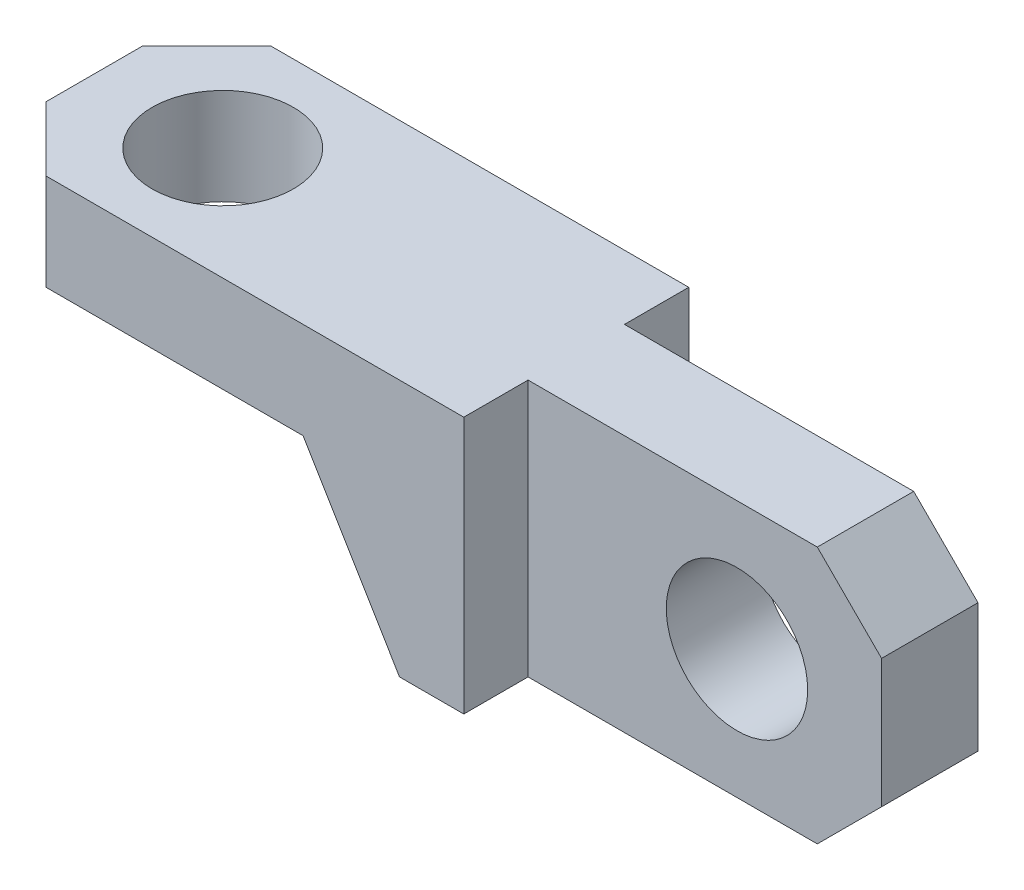
SolidWorks part; units mm, degrees
ref_plane "Front Plane" through (0, 0, 0) normal (0, 0, 1) x (1, 0, 0)
ref_plane "Top Plane" through (0, 0, 0) normal (0, 1, 0) x (1, 0, 0)
ref_plane "Right Plane" through (0, 0, 0) normal (1, 0, 0) x (0, 0, -1)
sketch "Sketch1" plane through (0, 0, 0) normal (0, 1, 0) x (1, 0, 0)
  line L0 (5.08, 0) -> (5.08, 8.89) construction
  line L1 (0, 0) -> (19.05, 0)
  line L2 (0, 0) -> (0, 8.89)
  line L3 (0, 8.89) -> (19.05, 8.89)
  line L4 (19.05, 0) -> (19.05, 8.89) construction
  line L5 (19.05, 6.35) -> (33.02, 6.35)
  line L6 (19.05, 8.89) -> (19.05, 6.35)
  line L7 (19.05, 0) -> (19.05, 2.54)
  line L8 (19.05, 2.54) -> (33.02, 2.54)
  line L9 (33.02, 2.54) -> (33.02, 6.35)
  circle A0 centre (5.08, 4.445) radius 2.794
  dimension "D3" = 5.588
  dimension "D1" = 19.05
  dimension "D2" = 8.89
  dimension "D4" = 5.08
  dimension "D5" = 3.81
  dimension "D6" = 13.97
extrude "base" add sketch "Sketch1" along normal blind 10.16
sketch "Sketch2" plane through (0, 0, -2.54) normal (0, 0, 1) x (1, 0, 0)
  line L0 (27.305, 10.16) -> (27.305, 0) construction
  line L1 (19.05, 10.16) -> (33.02, 10.16) construction
  line L2 (19.05, 0) -> (33.02, 0) construction
  line L3 (33.02, 10.16) -> (33.02, 0) construction
  circle A0 centre (27.305, 5.08) radius 2.794
  point P6 (23.992, 5.08)
  dimension "D1" = 5.588
  dimension "D2" = 5.715
extrude "latch_hole" cut sketch "Sketch2" against normal up to next
sketch "Sketch4" plane through (0, 0, 0) normal (0, 0, 1) x (1, 0, 0)
  line L0 (0, 6.35) -> (12.7, 6.35)
  line L1 (0, 10.16) -> (0, 0) construction
  line L2 (12.7, 6.35) -> (16.51, 0)
  line L3 (0, 0) -> (19.05, 0) construction
  line L4 (0, 6.35) -> (0, 0)
  line L5 (0, 0) -> (16.51, 0)
  dimension "D1" = 3.81
  dimension "D2" = 12.7
  dimension "D3" = 16.51
extrude "servo_arm_hole" cut sketch "Sketch4" against normal up to next
chamfer "Chamfer1" distance 2.54 angle 45 4 edges at (33.02, 0, -4.445) (33.02, 10.16, -4.445) (0, 8.255, -8.89) (0, 8.255, 0)
